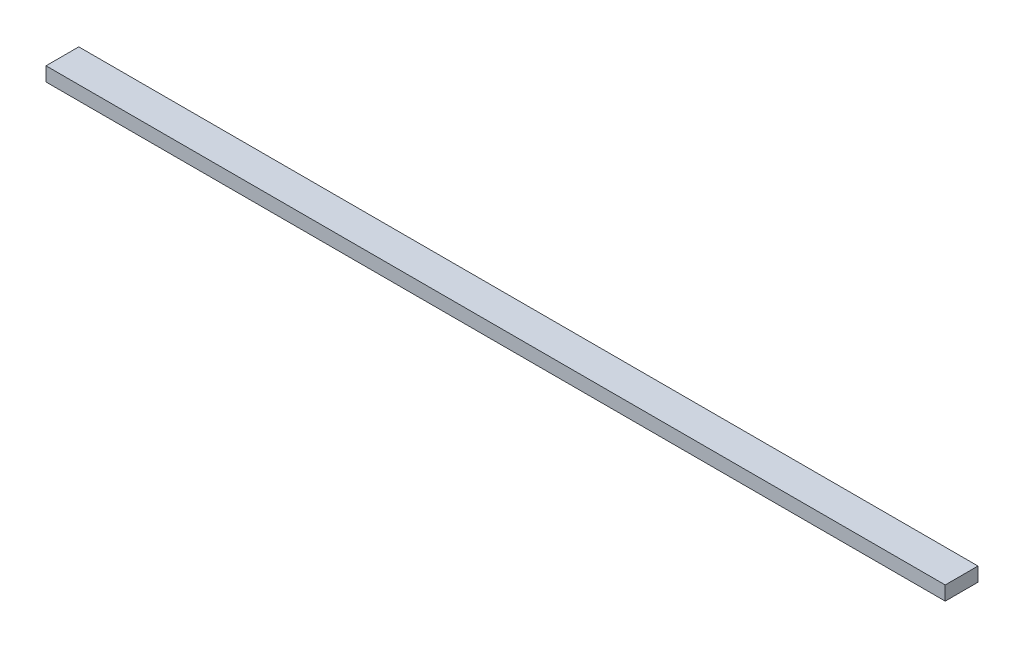
SolidWorks part; units mm, degrees
material "Pine"
ref_plane "Front Plane" through (0, 0, 0) normal (0, 0, 1) x (1, 0, 0)
ref_plane "Top Plane" through (0, 0, 0) normal (0, 1, 0) x (1, 0, 0)
ref_plane "Right Plane" through (0, 0, 0) normal (1, 0, 0) x (0, 0, -1)
sketch "Sketch1" plane through (0, 0, 0) normal (1, 0, 0) x (0, 0, -1)
  line L1 (0, 0) -> (88.9, 0)
  line L2 (0, 0) -> (0, 38.1)
  line L3 (0, 38.1) -> (88.9, 38.1)
  line L4 (88.9, 0) -> (88.9, 38.1)
  dimension "D1" = 38.1
  dimension "D2" = 88.9
extrude "Boss-Extrude1" add sketch "Sketch1" along normal blind 2438.4
